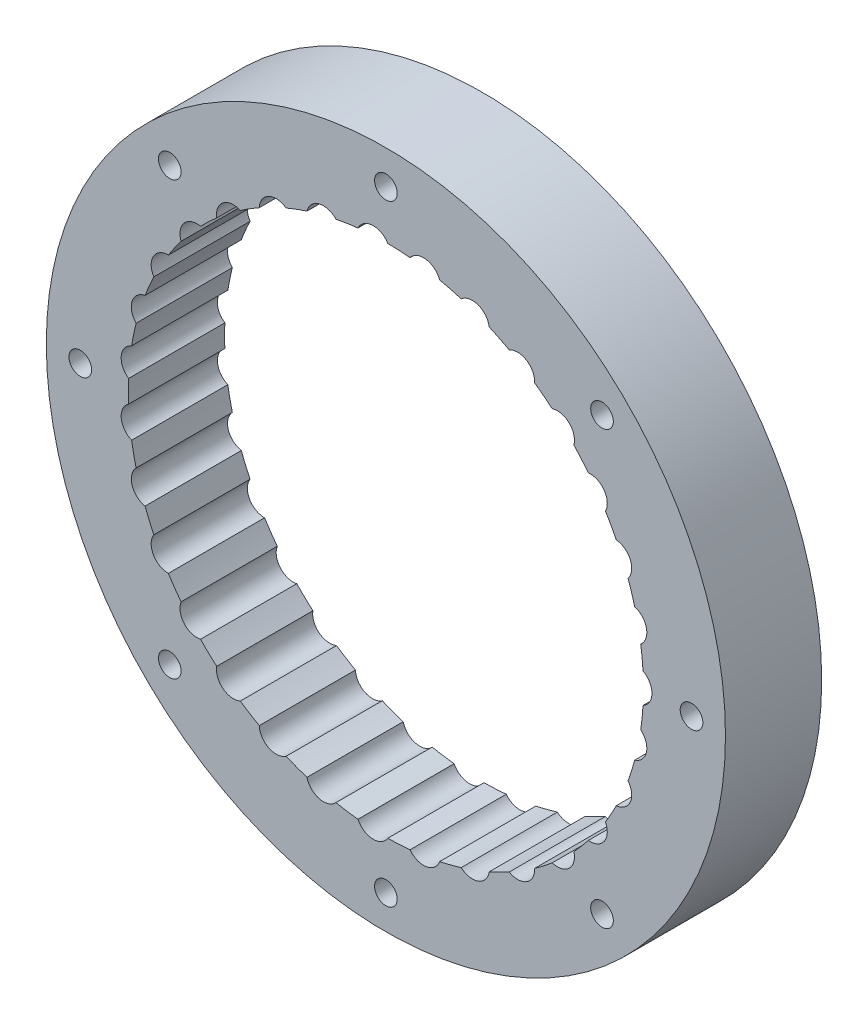
SolidWorks part; units mm, degrees
ref_plane "Front Plane" through (0, 0, 0) normal (0, 0, 1) x (1, 0, 0)
ref_plane "Top Plane" through (0, 0, 0) normal (0, 1, 0) x (1, 0, 0)
ref_plane "Right Plane" through (0, 0, 0) normal (1, 0, 0) x (0, 0, -1)
sketch "Sketch1" plane through (0, 0, 0) normal (0, 0, 1) x (1, 0, 0)
  line L0 (0, 0) -> (0, 60) construction
  line L1 (-2.2286, 43.9435) -> (0, 0) construction
  line L2 (0, 0) -> (44, 0) construction
  arc A0 (45.4233, -2.6409) -> (45.4233, 2.6409) centre (44, 0) ccw
  arc A1 (43.9619, -11.7305) -> (45.0251, -6.5568) centre (43.0993, -8.8571) ccw
  arc A2 (40.7006, -20.3398) -> (42.7835, -15.4861) centre (40.4341, -17.3517) ccw
  arc A3 (35.7731, -28.1164) -> (38.7904, -23.7813) centre (36.1136, -25.1358) ccw
  arc A4 (29.3811, -34.742) -> (33.2092, -31.103) centre (30.3145, -31.8909) ccw
  arc A5 (21.7861, -39.9451) -> (26.2685, -37.1513) centre (23.2744, -37.3403) ccw
  arc A6 (13.2993, -43.513) -> (18.2522, -41.6786) centre (15.2814, -41.2611) ccw
  arc A7 (4.2679, -45.2994) -> (9.4888, -44.4996) centre (6.6628, -43.4926) ccw
  arc A8 (-4.9381, -45.2312) -> (0.3368, -45.4988) centre (-2.2286, -43.9435) ccw
  arc A9 (-13.942, -43.3113) -> (-8.8289, -44.6352) centre (-11.0287, -42.5954) ccw
  arc A10 (-22.3751, -39.6182) -> (-17.6332, -41.9443) centre (-19.3773, -39.5034) ccw
  arc A11 (-29.8922, -34.3031) -> (-25.7155, -37.5361) centre (-26.9327, -34.7941) ccw
  arc A12 (-36.1855, -27.5837) -> (-32.7451, -31.5913) centre (-33.3854, -28.6604) ccw
  arc A13 (-40.9973, -19.735) -> (-38.4341, -24.3531) centre (-38.4713, -21.3533) ccw
  arc A14 (-44.1307, -11.0783) -> (-42.5496, -16.1178) centre (-41.9821, -13.172) ccw
  arc A15 (-45.4574, -1.9681) -> (-44.9231, -7.2227) centre (-43.7743, -4.4514) ccw
  arc A16 (-44.9231, 7.2227) -> (-45.4574, 1.9681) centre (-43.7743, 4.4514) ccw
  arc A17 (-42.5496, 16.1178) -> (-44.1307, 11.0783) centre (-41.9821, 13.172) ccw
  arc A18 (-38.4341, 24.3531) -> (-40.9973, 19.735) centre (-38.4713, 21.3533) ccw
  arc A19 (-32.7451, 31.5913) -> (-36.1855, 27.5837) centre (-33.3854, 28.6604) ccw
  arc A20 (-25.7155, 37.5361) -> (-29.8922, 34.3031) centre (-26.9327, 34.7941) ccw
  arc A21 (-17.6332, 41.9443) -> (-22.3751, 39.6182) centre (-19.3773, 39.5034) ccw
  arc A22 (-8.8289, 44.6352) -> (-13.942, 43.3113) centre (-11.0287, 42.5954) ccw
  arc A23 (0.3368, 45.4988) -> (-4.9381, 45.2312) centre (-2.2286, 43.9435) ccw
  arc A24 (9.4888, 44.4996) -> (4.2679, 45.2994) centre (6.6628, 43.4926) ccw
  arc A25 (18.2522, 41.6786) -> (13.2993, 43.513) centre (15.2814, 41.2611) ccw
  arc A26 (26.2685, 37.1513) -> (21.7861, 39.9451) centre (23.2744, 37.3403) ccw
  arc A27 (33.2092, 31.103) -> (29.3811, 34.742) centre (30.3145, 31.8909) ccw
  arc A28 (38.7904, 23.7813) -> (35.7731, 28.1164) centre (36.1136, 25.1358) ccw
  arc A29 (42.7835, 15.4861) -> (40.7006, 20.3398) centre (40.4341, 17.3517) ccw
  arc A30 (45.0251, 6.5568) -> (43.9619, 11.7305) centre (43.0993, 8.8571) ccw
  arc A31 (59.9241, 3.0179) -> (59.9241, -3.0179) centre (0, 0) ccw
  arc A32 (-4.9381, 45.2312) -> (-8.8289, 44.6352) centre (0, 0) ccw
  arc A33 (-13.942, 43.3113) -> (-17.6332, 41.9443) centre (0, 0) ccw
  arc A34 (-22.3751, 39.6182) -> (-25.7155, 37.5361) centre (0, 0) ccw
  arc A35 (-29.8922, 34.3031) -> (-32.7451, 31.5913) centre (0, 0) ccw
  arc A36 (-36.1855, 27.5837) -> (-38.4341, 24.3531) centre (0, 0) ccw
  arc A37 (-40.9973, 19.735) -> (-42.5496, 16.1178) centre (0, 0) ccw
  arc A38 (-44.1307, 11.0783) -> (-44.9231, 7.2227) centre (0, 0) ccw
  arc A39 (-45.4574, 1.9681) -> (-45.4574, -1.9681) centre (0, 0) ccw
  arc A40 (-44.9231, -7.2227) -> (-44.1307, -11.0783) centre (0, 0) ccw
  arc A41 (-42.5496, -16.1178) -> (-40.9973, -19.735) centre (0, 0) ccw
  arc A42 (-38.4341, -24.3531) -> (-36.1855, -27.5837) centre (0, 0) ccw
  arc A43 (-32.7451, -31.5913) -> (-29.8922, -34.3031) centre (0, 0) ccw
  arc A44 (-25.7155, -37.5361) -> (-22.3751, -39.6182) centre (0, 0) ccw
  arc A45 (-17.6332, -41.9443) -> (-13.942, -43.3113) centre (0, 0) ccw
  arc A46 (-8.8289, -44.6352) -> (-4.9381, -45.2312) centre (0, 0) ccw
  arc A47 (0.3368, -45.4988) -> (4.2679, -45.2994) centre (0, 0) ccw
  arc A48 (9.4888, -44.4996) -> (13.2993, -43.513) centre (0, 0) ccw
  arc A49 (18.2522, -41.6786) -> (21.7861, -39.9451) centre (0, 0) ccw
  arc A50 (26.2685, -37.1513) -> (29.3811, -34.742) centre (0, 0) ccw
  arc A51 (33.2092, -31.103) -> (35.7731, -28.1164) centre (0, 0) ccw
  arc A52 (38.7904, -23.7813) -> (40.7006, -20.3398) centre (0, 0) ccw
  arc A53 (42.7835, -15.4861) -> (43.9619, -11.7305) centre (0, 0) ccw
  arc A54 (45.0251, -6.5568) -> (45.4233, -2.6409) centre (0, 0) ccw
  arc A55 (45.4233, 2.6409) -> (45.0251, 6.5568) centre (0, 0) ccw
  arc A56 (43.9619, 11.7305) -> (42.7835, 15.4861) centre (0, 0) ccw
  arc A57 (40.7006, 20.3398) -> (38.7904, 23.7813) centre (0, 0) ccw
  arc A58 (35.7731, 28.1164) -> (33.2092, 31.103) centre (0, 0) ccw
  arc A59 (29.3811, 34.742) -> (26.2685, 37.1513) centre (0, 0) ccw
  arc A60 (4.2679, 45.2994) -> (0.3368, 45.4988) centre (0, 0) ccw
  arc A61 (13.2993, 43.513) -> (9.4888, 44.4996) centre (0, 0) ccw
  arc A62 (21.7861, 39.9451) -> (18.2522, 41.6786) centre (0, 0) ccw
  arc A63 (59.9241, -3.0179) -> (59.9241, 3.0179) centre (60, 0) ccw
  point P65 (0, 0)
  dimension "D1" = 6
  dimension "D4" = 91
  dimension "D2" = 44
  dimension "D3" = 31
extrude "Boss-Extrude1" add sketch "Sketch1" along normal blind 17
sketch "Sketch2" plane through (0, 0, 17) normal (0, 0, 1) x (1, 0, 0)
  line L0 (0, 0) -> (54, 0) construction
  circle A0 centre (0, 54) radius 2
  circle A1 centre (38.1838, 38.1838) radius 2
  circle A2 centre (54, 0) radius 2
  circle A3 centre (38.1838, -38.1838) radius 2
  circle A4 centre (0, -54) radius 2
  circle A5 centre (-38.1838, -38.1838) radius 2
  circle A6 centre (-54, 0) radius 2
  circle A7 centre (-38.1838, 38.1838) radius 2
  point P19 (0, 0)
  dimension "D3" = 4
  dimension "D1" = 54
  dimension "D2" = 8
extrude "Cut-Extrude1" cut sketch "Sketch2" against normal through all
sketch "Sketch3" plane through (0, 0, 17) normal (0, 0, 1) x (1, 0, 0)
  circle A0 centre (0, 0) radius 60
  circle A1 centre (0, 0) radius 75.5425
extrude "Cut-Extrude2" cut sketch "Sketch3" against normal blind 30
